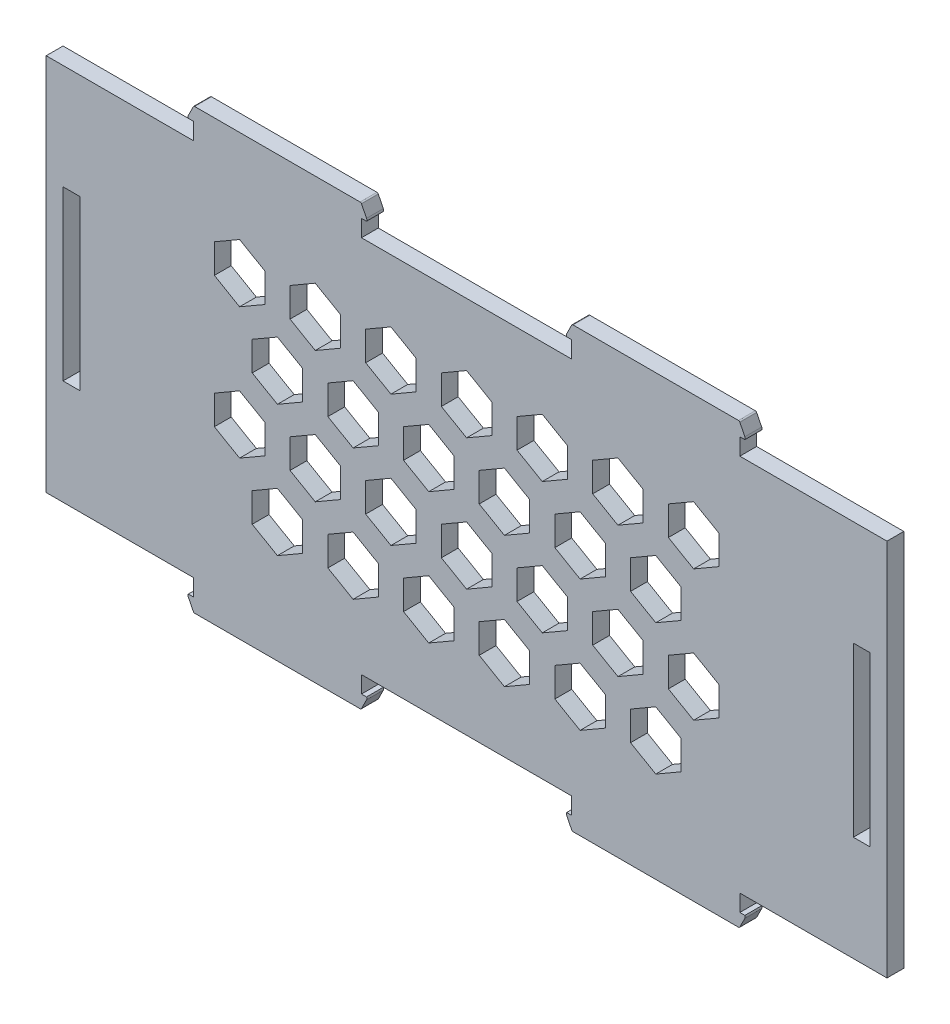
SolidWorks part; units mm, degrees
ref_plane "Front Plane" through (0, 0, 0) normal (0, 0, 1) x (1, 0, 0)
ref_plane "Top Plane" through (0, 0, 0) normal (0, 1, 0) x (1, 0, 0)
ref_plane "Right Plane" through (0, 0, 0) normal (1, 0, 0) x (0, 0, -1)
sketch "Sketch1" plane through (0, 0, 0) normal (0, 0, 1) x (1, 0, 0)
  line L0 (4, 0) -> (96, 0) construction
  line L1 (96, 0) -> (96, 45) construction
  line L2 (37.5, 0) -> (62.5, 0)
  line L3 (4, 45) -> (4, 0) construction
  line L8 (4, 22.5) -> (96, 22.5) construction
  line L30 (82.5, 0) -> (100, 0)
  line L44 (50, 45) -> (50, 0) construction
  line L45 (4, 32.5) -> (2, 32.5)
  line L46 (4, 32.5) -> (4, 12.5)
  line L47 (4, 12.5) -> (2, 12.5)
  line L48 (2, 32.5) -> (2, 12.5)
  line L49 (96, 32.5) -> (98, 32.5)
  line L50 (96, 32.5) -> (96, 12.5)
  line L51 (96, 12.5) -> (98, 12.5)
  line L52 (98, 32.5) -> (98, 12.5)
  line L69 (100, 0) -> (100, 45)
  line L77 (100, 45) -> (82.5, 45)
  line L99 (62.5, 45) -> (37.5, 45)
  line L100 (17.5, 45) -> (0, 45)
  line L101 (0, 45) -> (0, 0)
  line L110 (0, 0) -> (17.5, 0)
  line B0 (17.5, 0) -> (37.5, 0) construction
  line B1 (17.6618, -3.6) -> (37.3382, -3.6)
  line B2 (17.5, 0) -> (17.5, -2)
  line B3 (17.5, -3.5) -> (37.5, -3.5) construction
  line B4 (27.5, -3.5) -> (27.5, 0) construction
  line B5 (37.5, 0) -> (37.5, -2)
  line B6 (38.1, -2.3) -> (37.5, -3.5)
  line B7 (16.9, -2.3) -> (17.5, -3.5)
  line B8 (17.5, -2) -> (16.9, -2)
  line B9 (37.5, -2) -> (38.1, -2)
  arc B10 (17.5, -2) -> (16.9, -2.3) centre (17.2, -2.15) ccw construction
  arc B11 (17.5, -3.5) -> (17.6618, -3.6) centre (17.6618, -3.4191) ccw
  arc B12 (37.5, -3.5) -> (37.3382, -3.6) centre (37.3382, -3.4191) cw
  arc B13 (16.9, -2) -> (16.9, -2.3) centre (17.2, -2.15) ccw
  arc B14 (38.1, -2) -> (38.1, -2.3) centre (37.8, -2.15) cw
  line B15 (82.5, 0) -> (62.5, 0) construction
  line B16 (82.3382, -3.6) -> (62.6618, -3.6)
  line B17 (82.5, 0) -> (82.5, -2)
  line B18 (82.5, -3.5) -> (62.5, -3.5) construction
  line B19 (72.5, -3.5) -> (72.5, 0) construction
  line B20 (62.5, 0) -> (62.5, -2)
  line B21 (61.9, -2.3) -> (62.5, -3.5)
  line B22 (83.1, -2.3) -> (82.5, -3.5)
  line B23 (82.5, -2) -> (83.1, -2)
  line B24 (62.5, -2) -> (61.9, -2)
  arc B25 (82.5, -2) -> (83.1, -2.3) centre (82.8, -2.15) cw construction
  arc B26 (82.5, -3.5) -> (82.3382, -3.6) centre (82.3382, -3.4191) cw
  arc B27 (62.5, -3.5) -> (62.6618, -3.6) centre (62.6618, -3.4191) ccw
  arc B28 (83.1, -2) -> (83.1, -2.3) centre (82.8, -2.15) cw
  arc B29 (61.9, -2) -> (61.9, -2.3) centre (62.2, -2.15) ccw
  line B30 (82.5, 45) -> (62.5, 45) construction
  line B31 (82.3382, 48.6) -> (62.6618, 48.6)
  line B32 (82.5, 45) -> (82.5, 47)
  line B33 (82.5, 48.5) -> (62.5, 48.5) construction
  line B34 (72.5, 48.5) -> (72.5, 45) construction
  line B35 (62.5, 45) -> (62.5, 47)
  line B36 (61.9, 47.3) -> (62.5, 48.5)
  line B37 (83.1, 47.3) -> (82.5, 48.5)
  line B38 (82.5, 47) -> (83.1, 47)
  line B39 (62.5, 47) -> (61.9, 47)
  arc B40 (82.5, 47) -> (83.1, 47.3) centre (82.8, 47.15) ccw construction
  arc B41 (82.5, 48.5) -> (82.3382, 48.6) centre (82.3382, 48.4191) ccw
  arc B42 (62.5, 48.5) -> (62.6618, 48.6) centre (62.6618, 48.4191) cw
  arc B43 (83.1, 47) -> (83.1, 47.3) centre (82.8, 47.15) ccw
  arc B44 (61.9, 47) -> (61.9, 47.3) centre (62.2, 47.15) cw
  line B45 (17.5, 45) -> (37.5, 45) construction
  line B46 (17.6618, 48.6) -> (37.3382, 48.6)
  line B47 (17.5, 45) -> (17.5, 47)
  line B48 (17.5, 48.5) -> (37.5, 48.5) construction
  line B49 (27.5, 48.5) -> (27.5, 45) construction
  line B50 (37.5, 45) -> (37.5, 47)
  line B51 (38.1, 47.3) -> (37.5, 48.5)
  line B52 (16.9, 47.3) -> (17.5, 48.5)
  line B53 (17.5, 47) -> (16.9, 47)
  line B54 (37.5, 47) -> (38.1, 47)
  arc B55 (17.5, 47) -> (16.9, 47.3) centre (17.2, 47.15) cw construction
  arc B56 (17.5, 48.5) -> (17.6618, 48.6) centre (17.6618, 48.4191) cw
  arc B57 (37.5, 48.5) -> (37.3382, 48.6) centre (37.3382, 48.4191) ccw
  arc B58 (16.9, 47) -> (16.9, 47.3) centre (17.2, 47.15) cw
  arc B59 (38.1, 47) -> (38.1, 47.3) centre (37.8, 47.15) ccw
  dimension "D3" = 45
  dimension "D4" = 2
  dimension "D16" = 45
  dimension "D17" = 20
  dimension "D18" = 2
  dimension "D20" = 46
sketch_block_instance "insert_bloquant_20mm-2mm-1"
sketch_block "insert_bloquant_20mm-2mm" parameters "D1"=2, "D2"=1.5, "D3"=1.2, "D4"=20, "D5"=0.1, "D6"=0.6
sketch_block_instance "insert_bloquant_20mm-2mm-4"
sketch_block_instance "insert_bloquant_20mm-2mm-5"
sketch_block_instance "insert_bloquant_20mm-2mm-6"
extrude "Boss-Extrude1" add sketch "Sketch1" along normal blind 2 contours B54 B59 B51 B57 B46 B56 B52 B58 B53 B47 L100 L101 L110 B2 B8 B13 B7 B11 B1 B12 B6 B14 B9 B5 L2 B20 B24 B29 B21 B27 B16 B26 B22 B28 B23 B17 L30 L69 L77 B32 B38 B43 B37 B41 B31 B42 B36 B44 B39 B35 L99
sketch "Sketch2" plane through (0, 0, 2) normal (0, 0, 1) x (1, 0, 0)
  line L107 (50, 45) -> (50, 0) construction
  line L108 (37.5, 0) -> (62.5, 0) construction
  line L109 (62.5, 45) -> (37.5, 45) construction
  line B0 (20, 32.3707) -> (23, 30.6387)
  line B1 (27.5, 31.5047) -> (23, 28.9066) construction
  line B2 (23, 28.9066) -> (23, 23.7105) construction
  line B3 (23, 23.7105) -> (27.5, 21.1124) construction
  line B4 (27.5, 21.1124) -> (32, 23.7105) construction
  line B5 (32, 23.7105) -> (32, 28.9066) construction
  line B6 (32, 28.9066) -> (27.5, 31.5047) construction
  line B7 (23, 39.2989) -> (18.5, 36.7009) construction
  line B8 (18.5, 36.7009) -> (18.5, 31.5047) construction
  line B9 (18.5, 31.5047) -> (23, 28.9066) construction
  line B10 (23, 30.6387) -> (26, 32.3707)
  line B11 (30.5, 28.0406) -> (27.5, 29.7727)
  line B12 (24.5, 28.0406) -> (24.5, 24.5765)
  line B13 (24.5, 24.5765) -> (27.5, 22.8445)
  line B14 (27.5, 22.8445) -> (30.5, 24.5765)
  line B15 (29, 35.8348) -> (29, 32.3707)
  line B16 (29, 32.3707) -> (32, 30.6387)
  line B17 (32, 30.6387) -> (35, 32.3707)
  line B18 (39.5, 28.0406) -> (36.5, 29.7727)
  line B19 (33.5, 28.0406) -> (33.5, 24.5765)
  line B20 (33.5, 24.5765) -> (36.5, 22.8445)
  line B21 (36.5, 22.8445) -> (39.5, 24.5765)
  line B22 (44, 35.8348) -> (41, 37.5669)
  line B23 (38, 35.8348) -> (38, 32.3707)
  line B24 (38, 32.3707) -> (41, 30.6387)
  line B25 (41, 30.6387) -> (44, 32.3707)
  line B26 (48.5, 28.0406) -> (45.5, 29.7727)
  line B27 (42.5, 28.0406) -> (42.5, 24.5765)
  line B28 (42.5, 24.5765) -> (45.5, 22.8445)
  line B29 (45.5, 22.8445) -> (48.5, 24.5765)
  line B30 (53, 35.8348) -> (50, 37.5669)
  line B31 (56, 35.8348) -> (56, 32.3707)
  line B32 (23, 37.5669) -> (20, 35.8348)
  line B33 (47, 35.8348) -> (47, 32.3707)
  line B34 (47, 32.3707) -> (50, 30.6387)
  line B35 (50, 30.6387) -> (53, 32.3707)
  line B36 (56, 32.3707) -> (59, 30.6387)
  line B37 (59, 30.6387) -> (62, 32.3707)
  line B38 (66.5, 28.0406) -> (63.5, 29.7727)
  line B39 (60.5, 28.0406) -> (60.5, 24.5765)
  line B40 (60.5, 24.5765) -> (63.5, 22.8445)
  line B41 (63.5, 22.8445) -> (66.5, 24.5765)
  line B42 (71, 35.8348) -> (68, 37.5669)
  line B43 (65, 35.8348) -> (65, 32.3707)
  line B44 (65, 32.3707) -> (68, 30.6387)
  line B45 (68, 30.6387) -> (71, 32.3707)
  line B46 (75.5, 28.0406) -> (72.5, 29.7727)
  line B47 (69.5, 28.0406) -> (69.5, 24.5765)
  line B48 (69.5, 24.5765) -> (72.5, 22.8445)
  line B49 (72.5, 22.8445) -> (75.5, 24.5765)
  line B50 (80, 35.8348) -> (77, 37.5669)
  line B51 (74, 35.8348) -> (74, 32.3707)
  line B52 (74, 32.3707) -> (77, 30.6387)
  line B53 (77, 30.6387) -> (80, 32.3707)
  line B54 (51.5, 24.5765) -> (54.5, 22.8445)
  line B55 (54.5, 22.8445) -> (57.5, 24.5765)
  line B56 (27.5, 36.7009) -> (23, 39.2989) construction
  line B57 (23, 28.9066) -> (27.5, 31.5047) construction
  line B58 (27.5, 31.5047) -> (27.5, 36.7009) construction
  line B59 (26, 35.8348) -> (23, 37.5669)
  line B60 (20, 35.8348) -> (20, 32.3707)
  line B61 (26, 32.3707) -> (26, 35.8348)
  line B62 (27.5, 29.7727) -> (24.5, 28.0406)
  line B63 (30.5, 24.5765) -> (30.5, 28.0406)
  line B64 (23, 34.1028) -> (27.5, 26.3086) construction
  line B65 (71, 32.3707) -> (71, 35.8348)
  line B66 (68, 37.5669) -> (65, 35.8348)
  line B67 (53, 32.3707) -> (53, 35.8348)
  line B68 (50, 37.5669) -> (47, 35.8348)
  line B69 (23, 34.1028) -> (80, 34.1028) construction
  line B70 (35, 32.3707) -> (35, 35.8348)
  line B71 (35, 35.8348) -> (32, 37.5669)
  line B72 (32, 37.5669) -> (29, 35.8348)
  line B73 (39.5, 24.5765) -> (39.5, 28.0406)
  line B74 (36.5, 29.7727) -> (33.5, 28.0406)
  line B75 (77, 37.5669) -> (74, 35.8348)
  line B76 (80, 32.3707) -> (80, 35.8348)
  line B77 (81.5, 29.7727) -> (78.5, 28.0406)
  line B78 (84.5, 28.0406) -> (81.5, 29.7727)
  line B79 (84.5, 24.5765) -> (84.5, 28.0406)
  line B80 (81.5, 22.8445) -> (84.5, 24.5765)
  line B81 (78.5, 24.5765) -> (81.5, 22.8445)
  line B82 (78.5, 28.0406) -> (78.5, 24.5765)
  line B83 (72.5, 29.7727) -> (69.5, 28.0406)
  line B84 (75.5, 24.5765) -> (75.5, 28.0406)
  line B85 (59, 37.5669) -> (56, 35.8348)
  line B86 (62, 35.8348) -> (59, 37.5669)
  line B87 (62, 32.3707) -> (62, 35.8348)
  line B88 (63.5, 29.7727) -> (60.5, 28.0406)
  line B89 (66.5, 24.5765) -> (66.5, 28.0406)
  line B90 (54.5, 29.7727) -> (51.5, 28.0406)
  line B91 (57.5, 28.0406) -> (54.5, 29.7727)
  line B92 (57.5, 24.5765) -> (57.5, 28.0406)
  line B93 (51.5, 28.0406) -> (51.5, 24.5765)
  line B94 (41, 37.5669) -> (38, 35.8348)
  line B95 (44, 32.3707) -> (44, 35.8348)
  line B96 (45.5, 29.7727) -> (42.5, 28.0406)
  line B97 (48.5, 24.5765) -> (48.5, 28.0406)
  circle B98 centre (27.5, 26.3086) radius 4.5 construction
  circle B99 centre (23, 34.1028) radius 4.5 construction
  circle B100 centre (23, 34.1028) radius 3 construction
  circle B101 centre (27.5, 26.3086) radius 3 construction
  line B102 (20, 16.7823) -> (23, 15.0502)
  line B103 (23, 15.0502) -> (26, 16.7823)
  line B104 (30.5, 12.4521) -> (27.5, 14.1842)
  line B105 (24.5, 12.4521) -> (24.5, 8.988)
  line B106 (24.5, 8.988) -> (27.5, 7.256)
  line B107 (27.5, 7.256) -> (30.5, 8.988)
  line B108 (29, 20.2464) -> (29, 16.7823)
  line B109 (29, 16.7823) -> (32, 15.0502)
  line B110 (32, 15.0502) -> (35, 16.7823)
  line B111 (39.5, 12.4521) -> (36.5, 14.1842)
  line B112 (33.5, 12.4521) -> (33.5, 8.988)
  line B113 (33.5, 8.988) -> (36.5, 7.256)
  line B114 (36.5, 7.256) -> (39.5, 8.988)
  line B115 (44, 20.2464) -> (41, 21.9784)
  line B116 (38, 20.2464) -> (38, 16.7823)
  line B117 (38, 16.7823) -> (41, 15.0502)
  line B118 (41, 15.0502) -> (44, 16.7823)
  line B119 (48.5, 12.4521) -> (45.5, 14.1842)
  line B120 (42.5, 12.4521) -> (42.5, 8.988)
  line B121 (42.5, 8.988) -> (45.5, 7.256)
  line B122 (45.5, 7.256) -> (48.5, 8.988)
  line B123 (53, 20.2464) -> (50, 21.9784)
  line B124 (56, 20.2464) -> (56, 16.7823)
  line B125 (23, 21.9784) -> (20, 20.2464)
  line B126 (47, 20.2464) -> (47, 16.7823)
  line B127 (47, 16.7823) -> (50, 15.0502)
  line B128 (50, 15.0502) -> (53, 16.7823)
  line B129 (56, 16.7823) -> (59, 15.0502)
  line B130 (59, 15.0502) -> (62, 16.7823)
  line B131 (66.5, 12.4521) -> (63.5, 14.1842)
  line B132 (60.5, 12.4521) -> (60.5, 8.988)
  line B133 (60.5, 8.988) -> (63.5, 7.256)
  line B134 (63.5, 7.256) -> (66.5, 8.988)
  line B135 (71, 20.2464) -> (68, 21.9784)
  line B136 (65, 20.2464) -> (65, 16.7823)
  line B137 (65, 16.7823) -> (68, 15.0502)
  line B138 (68, 15.0502) -> (71, 16.7823)
  line B139 (75.5, 12.4521) -> (72.5, 14.1842)
  line B140 (69.5, 12.4521) -> (69.5, 8.988)
  line B141 (69.5, 8.988) -> (72.5, 7.256)
  line B142 (72.5, 7.256) -> (75.5, 8.988)
  line B143 (80, 20.2464) -> (77, 21.9784)
  line B144 (74, 20.2464) -> (74, 16.7823)
  line B145 (74, 16.7823) -> (77, 15.0502)
  line B146 (77, 15.0502) -> (80, 16.7823)
  line B147 (51.5, 8.988) -> (54.5, 7.256)
  line B148 (54.5, 7.256) -> (57.5, 8.988)
  line B149 (26, 20.2464) -> (23, 21.9784)
  line B150 (20, 20.2464) -> (20, 16.7823)
  line B151 (26, 16.7823) -> (26, 20.2464)
  line B152 (27.5, 14.1842) -> (24.5, 12.4521)
  line B153 (30.5, 8.988) -> (30.5, 12.4521)
  line B154 (71, 16.7823) -> (71, 20.2464)
  line B155 (68, 21.9784) -> (65, 20.2464)
  line B156 (53, 16.7823) -> (53, 20.2464)
  line B157 (50, 21.9784) -> (47, 20.2464)
  line B158 (35, 16.7823) -> (35, 20.2464)
  line B159 (35, 20.2464) -> (32, 21.9784)
  line B160 (32, 21.9784) -> (29, 20.2464)
  line B161 (39.5, 8.988) -> (39.5, 12.4521)
  line B162 (36.5, 14.1842) -> (33.5, 12.4521)
  line B163 (77, 21.9784) -> (74, 20.2464)
  line B164 (80, 16.7823) -> (80, 20.2464)
  line B165 (72.5, 14.1842) -> (69.5, 12.4521)
  line B166 (75.5, 8.988) -> (75.5, 12.4521)
  line B167 (59, 21.9784) -> (56, 20.2464)
  line B168 (62, 20.2464) -> (59, 21.9784)
  line B169 (62, 16.7823) -> (62, 20.2464)
  line B170 (63.5, 14.1842) -> (60.5, 12.4521)
  line B171 (66.5, 8.988) -> (66.5, 12.4521)
  line B172 (54.5, 14.1842) -> (51.5, 12.4521)
  line B173 (57.5, 12.4521) -> (54.5, 14.1842)
  line B174 (57.5, 8.988) -> (57.5, 12.4521)
  line B175 (51.5, 12.4521) -> (51.5, 8.988)
  line B176 (41, 21.9784) -> (38, 20.2464)
  line B177 (44, 16.7823) -> (44, 20.2464)
  line B178 (45.5, 14.1842) -> (42.5, 12.4521)
  line B179 (48.5, 8.988) -> (48.5, 12.4521)
sketch_block_instance "Alveole_12mm_4mm_8x2-3"
sketch_block "Alveole_12mm_4mm_8x2" parameters "D1"=7, "D2"=1.5, "D3"=13.2857, "D4"=14
sketch_block_instance "Alveole_12mm_4mm_8x2-5"
extrude "Cut-Extrude1" cut sketch "Sketch2" against normal through all
